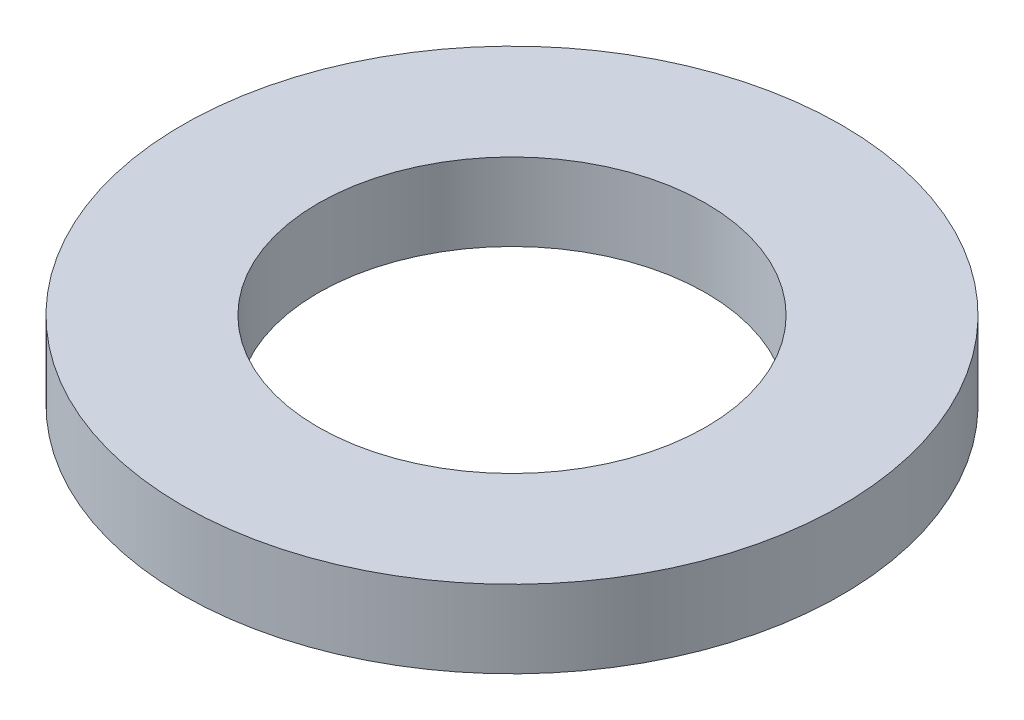
SolidWorks part; units mm, degrees
ref_plane "정면" through (0, 0, 0) normal (0, 0, 1) x (1, 0, 0)
ref_plane "윗면" through (0, 0, 0) normal (0, 1, 0) x (1, 0, 0)
ref_plane "우측면" through (0, 0, 0) normal (1, 0, 0) x (0, 0, -1)
sketch "스케치1" plane through (0, 0, 0) normal (0, 1, 0) x (1, 0, 0)
  circle A0 centre (0, 0) radius 12.75
  circle A1 centre (0, 0) radius 7.5
  dimension "D1" = 25.5
  dimension "D2" = 15
extrude "보스-돌출1" add sketch "스케치1" along normal blind 3
